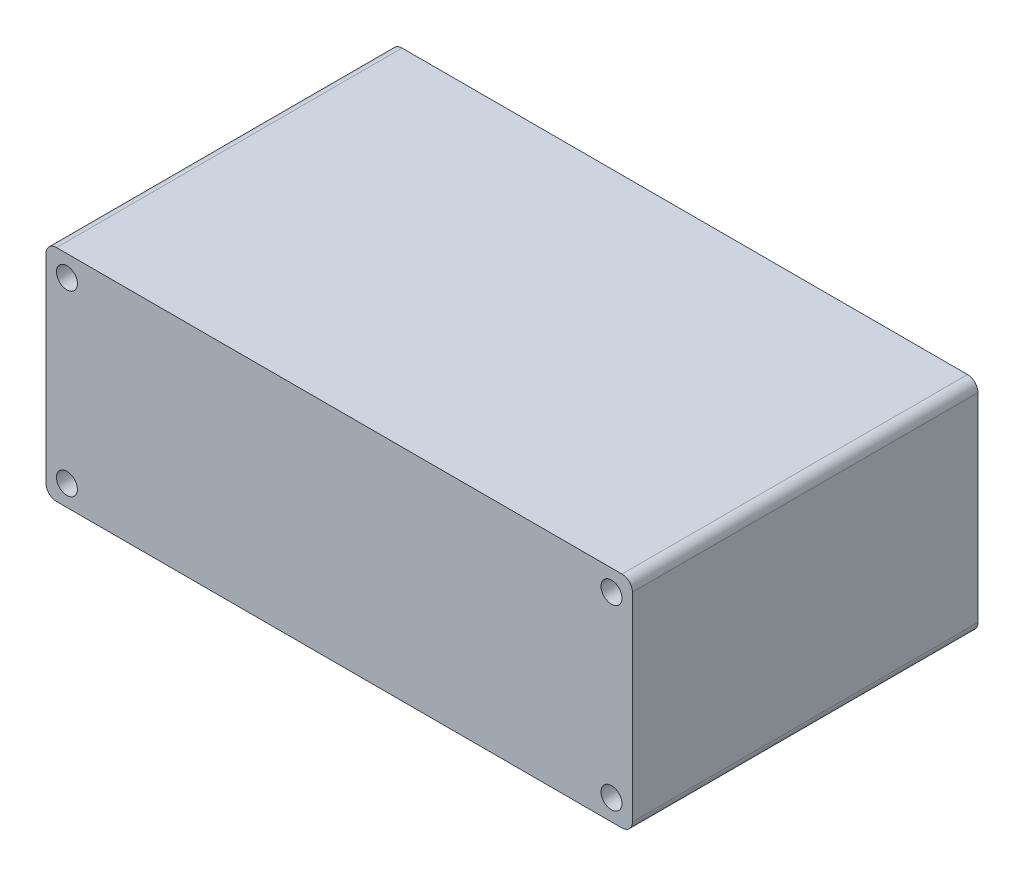
SolidWorks part; units mm, degrees
ref_plane "Front Plane" through (0, 0, 0) normal (0, 0, 1) x (1, 0, 0)
ref_plane "Top Plane" through (0, 0, 0) normal (0, 1, 0) x (1, 0, 0)
ref_plane "Right Plane" through (0, 0, 0) normal (1, 0, 0) x (0, 0, -1)
sketch "Sketch1" plane through (0, 0, 0) normal (0, 0, 1) x (1, 0, 0)
  line L0 (131.5, -11.5) -> (96.5, -11.5) construction
  line L1 (131.5, -21) -> (96.5, -21)
  line L2 (131.5, -2) -> (96.5, -2)
  line L4 (141, -22) -> (87, -22)
  line L5 (142, -21) -> (142, -2)
  line L6 (141, -1) -> (87, -1)
  line L7 (86, -21) -> (86, -2)
  arc A0 (131.5, -21) -> (131.5, -2) centre (131.5, -11.5) ccw
  arc A1 (96.5, -2) -> (96.5, -21) centre (96.5, -11.5) ccw
  circle A2 centre (140, -3) radius 1 construction
  circle A3 centre (88, -3) radius 1 construction
  circle A4 centre (88, -20) radius 1 construction
  circle A5 centre (140, -20) radius 1 construction
  circle A6 centre (140, -3) radius 1
  circle A7 centre (88, -3) radius 1
  circle A8 centre (88, -20) radius 1
  circle A9 centre (140, -20) radius 1
  circle A10 centre (131.5, -11.5) radius 8.5 construction
  arc A11 (142, -2) -> (141, -1) centre (141, -2) ccw
  arc A12 (87, -1) -> (86, -2) centre (87, -2) ccw
  arc A13 (87, -22) -> (86, -21) centre (87, -21) cw
  arc A14 (141, -22) -> (142, -21) centre (141, -21) ccw
  point P4 (114, -11.5)
  point P27 (141, -11.5)
  point P28 (87, -11.5)
  dimension "D1" = 1
  dimension "D6" = 1
  dimension "D2" = 1
  dimension "D3" = 1
  dimension "D4" = 1
  dimension "D5" = 1
extrude "Boss-Extrude1" add sketch "Sketch1" along normal blind 30
sketch "Sketch3" plane through (0, 0, 30) normal (0, 0, 1) x (1, 0, 0)
  line L0 (86, -2) -> (86, -21) construction
  line L1 (141, -1) -> (87, -1) construction
  line L2 (87, -22) -> (141, -22) construction
  line L3 (142, -21) -> (142, -2) construction
  line L4 (86, -2) -> (86, -21)
  line L5 (141, -1) -> (87, -1)
  line L6 (87, -22) -> (141, -22)
  line L7 (142, -21) -> (142, -2)
  arc A0 (86, -21) -> (87, -22) centre (87, -21) ccw construction
  arc A1 (87, -1) -> (86, -2) centre (87, -2) ccw construction
  arc A2 (142, -2) -> (141, -1) centre (141, -2) ccw construction
  arc A3 (141, -22) -> (142, -21) centre (141, -21) ccw construction
  arc A4 (86, -21) -> (87, -22) centre (87, -21) ccw
  arc A5 (87, -1) -> (86, -2) centre (87, -2) ccw
  arc A6 (142, -2) -> (141, -1) centre (141, -2) ccw
  arc A7 (141, -22) -> (142, -21) centre (141, -21) ccw
  circle A8 centre (88, -3) radius 1 construction
  circle A9 centre (88, -20) radius 1 construction
  circle A10 centre (140, -20) radius 1 construction
  circle A11 centre (140, -3) radius 1 construction
  circle A12 centre (88, -3) radius 1
  circle A13 centre (88, -20) radius 1
  circle A14 centre (140, -20) radius 1
  circle A15 centre (140, -3) radius 1
extrude "Boss-Extrude2" add sketch "Sketch3" along normal blind 3
sketch "Sketch4" plane through (86, 0, 0) normal (-1, 0, 0) x (0, 0, 1)
  line L1 (33, -2) -> (33, -21) construction
  circle A0 centre (23, -11.5) radius 5
  point P5 (33, -11.5)
  dimension "D2" = 10
  dimension "D1" = 10
extrude "Cut-Extrude1" cut sketch "Sketch4" against normal up to next contours A0
